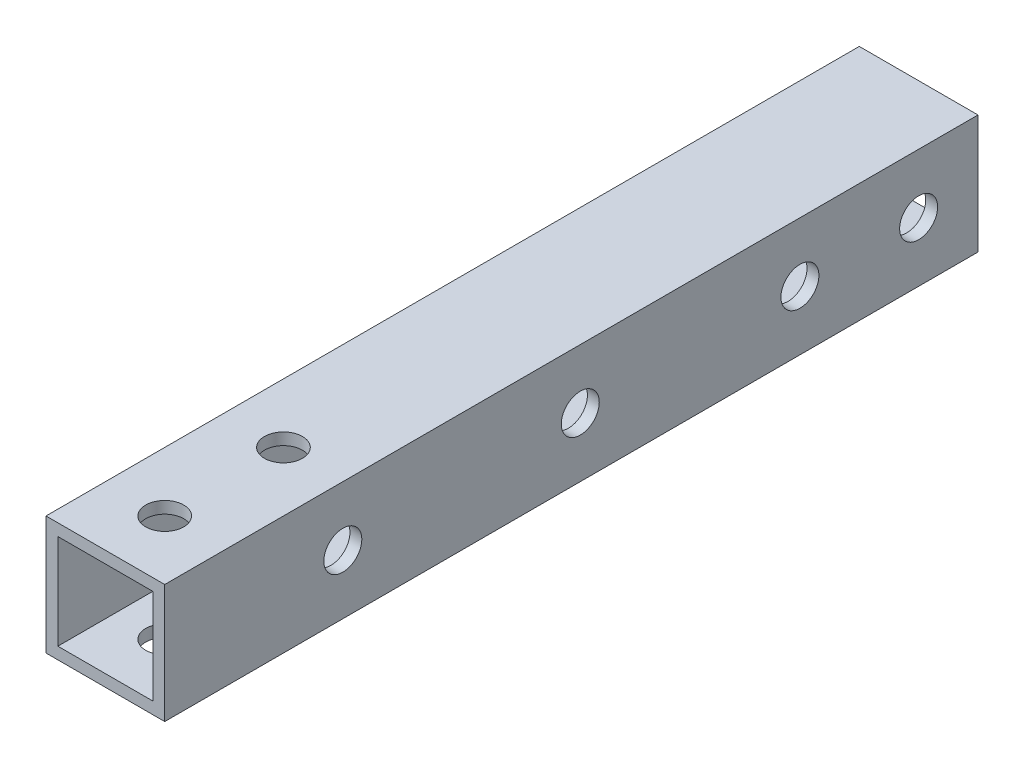
SolidWorks part; units mm, degrees
material "1060 合金"
ref_plane "正面" through (0, 0, 0) normal (0, 0, 1) x (1, 0, 0)
ref_plane "平面" through (0, 0, 0) normal (0, 1, 0) x (1, 0, 0)
ref_plane "右側面" through (0, 0, 0) normal (1, 0, 0) x (0, 0, -1)
sketch "ｽｹｯﾁ1" plane through (0, 0, 0) normal (0, 0, 1) x (1, 0, 0)
  line L1 (5, 5) -> (-5, 5)
  line L2 (5, 5) -> (5, -5)
  line L3 (5, -5) -> (-5, -5)
  line L4 (-5, 5) -> (-5, -5)
  line L5 (5, 5) -> (-5, -5) construction
  line L6 (5, -5) -> (-5, 5) construction
  point P0 (0, 0)
  dimension "D1" = 10
  dimension "D2" = 10
extrude "押し出し-薄板1" add sketch "ｽｹｯﾁ1" along normal blind 68.5 thin thin type one direction reverse wall 1
sketch "ｽｹｯﾁ2" plane through (0, 5, 0) normal (0, 1, 0) x (1, 0, 0)
  line L0 (0, 0) -> (0, -68.5) construction
  line L1 (5, -68.5) -> (-5, -68.5) construction
  circle A0 centre (0, -63.5) radius 1.6
  circle A1 centre (0, -53.5) radius 1.6
  dimension "D1" = 10
  dimension "D2" = 5
  dimension "D3" = 3.2
extrude "ｶｯﾄ - 押し出し1" cut sketch "ｽｹｯﾁ2" against normal through all
sketch "ｽｹｯﾁ3" plane through (5, 0, 0) normal (1, 0, 0) x (0, 0, -1)
  line L0 (0, 0) -> (-68.5, 0) construction
  line L1 (-68.5, -5) -> (-68.5, 5) construction
  line L2 (0, -5) -> (0, 5) construction
  circle A0 centre (-5, 0) radius 1.6
  circle A2 centre (-15, 0) radius 1.6
  dimension "D1" = 5
  dimension "D2" = 3.2
  dimension "D3" = 10
  dimension "D6" = 3.2
extrude "ｶｯﾄ - 押し出し2" cut sketch "ｽｹｯﾁ3" against normal through all
sketch "ｽｹｯﾁ4" plane through (5, 0, 0) normal (1, 0, 0) x (0, 0, -1)
  line L0 (-68.5, 0) -> (0, 0) construction
  line L1 (-68.5, -5) -> (-68.5, 5) construction
  circle A0 centre (-53.5, 0) radius 1.6
  circle A1 centre (-33.5, 0) radius 1.6
  dimension "D1" = 20
  dimension "D2" = 15
  dimension "D3" = 3.2
extrude "ｶｯﾄ - 押し出し3" cut sketch "ｽｹｯﾁ4" against normal through all
